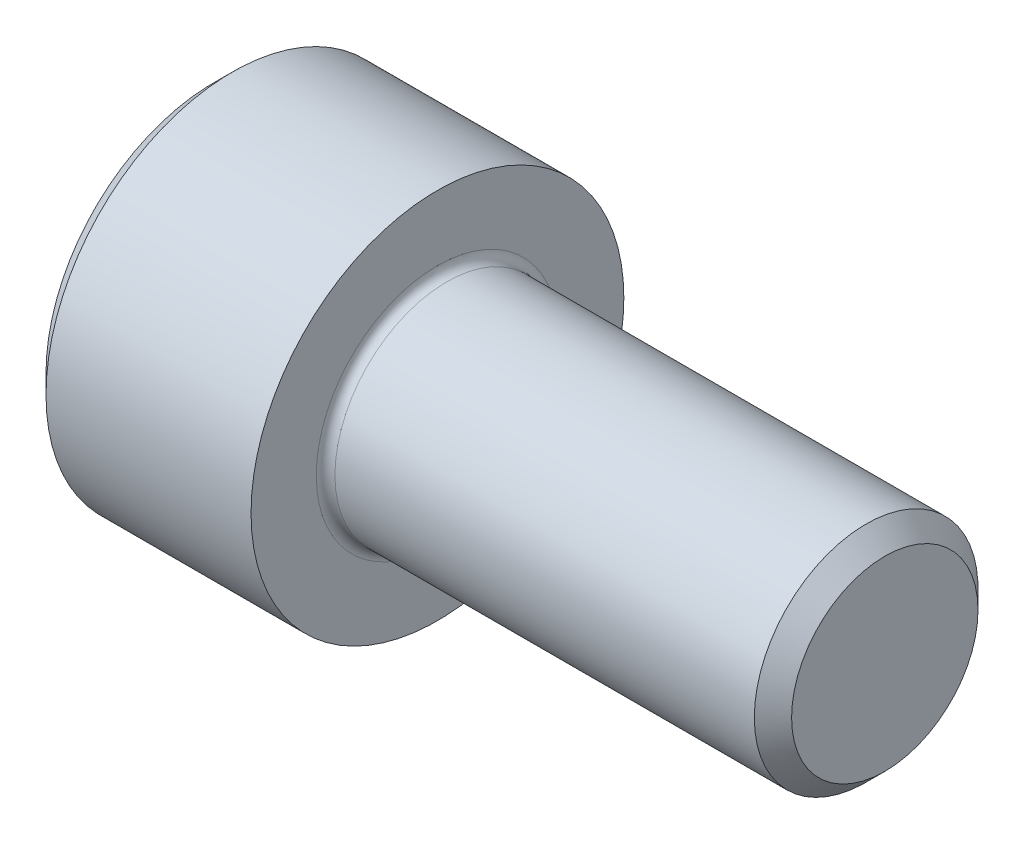
SolidWorks part; units mm, degrees
material "AISI 4340 Steel, normalized"
ref_plane "Front Plane" through (0, 0, 0) normal (0, 0, 1) x (1, 0, 0)
ref_plane "Top Plane" through (0, 0, 0) normal (0, 1, 0) x (1, 0, 0)
ref_plane "Right Plane" through (0, 0, 0) normal (1, 0, 0) x (0, 0, -1)
sketch "Sketch1" plane through (0, 0, 0) normal (0, 0, 1) x (1, 0, 0)
  line L0 (0, 0) -> (0, 5)
  line L1 (0, 5) -> (6, 5)
  line L2 (6, 5) -> (6, 3.25)
  line L3 (6.25, 3) -> (18, 3)
  line L4 (18, 3) -> (18, 0)
  line L5 (0, 0) -> (18, 0)
  arc A0 (6, 3.25) -> (6.25, 3) centre (6.25, 3.25) ccw
  point P9 (6, 3)
  dimension "D5" = 0.25
  dimension "D1" = 12
  dimension "D2" = 6
  dimension "D3" = 5
  dimension "D4" = 3
revolve "Revolve1" add sketch "Sketch1" angle 360 about L5
cosmetic thread "Cosmetic Thread1" parameters "D1"=11, "D2"=4.891
chamfer "Chamfer1" distance 0.5 angle 45 2 edges at (0, 0, 5) (18, 0, 3)
sketch "Sketch2" plane through (0, 0, 0) normal (-1, 0, 0) x (0, 0, 1)
  line L1 (0, -2.5) -> (2.1651, -1.25)
  line L2 (2.1651, -1.25) -> (2.1651, 1.25)
  line L3 (2.1651, 1.25) -> (0, 2.5)
  line L4 (0, 2.5) -> (-2.1651, 1.25)
  line L5 (-2.1651, 1.25) -> (-2.1651, -1.25)
  line L6 (-2.1651, -1.25) -> (0, -2.5)
  circle A0 centre (0, 0) radius 2.1651 construction
  dimension "D1" = 5
extrude "Cut-Extrude1" cut sketch "Sketch2" against normal blind 3
sketch "Sketch3" plane through (0, 0, 0) normal (0, 0, 1) x (1, 0, 0)
  line L0 (3, 2.5) -> (3, 0)
  line L1 (3, -1.25) -> (3, 1.25) construction
  line L2 (3, 0) -> (4.5, 0)
  line L3 (3, 2.5) -> (4.5, 0)
  dimension "D1" = 1.5
revolve "Cut-Revolve1" cut sketch "Sketch3" angle 360 about L2
